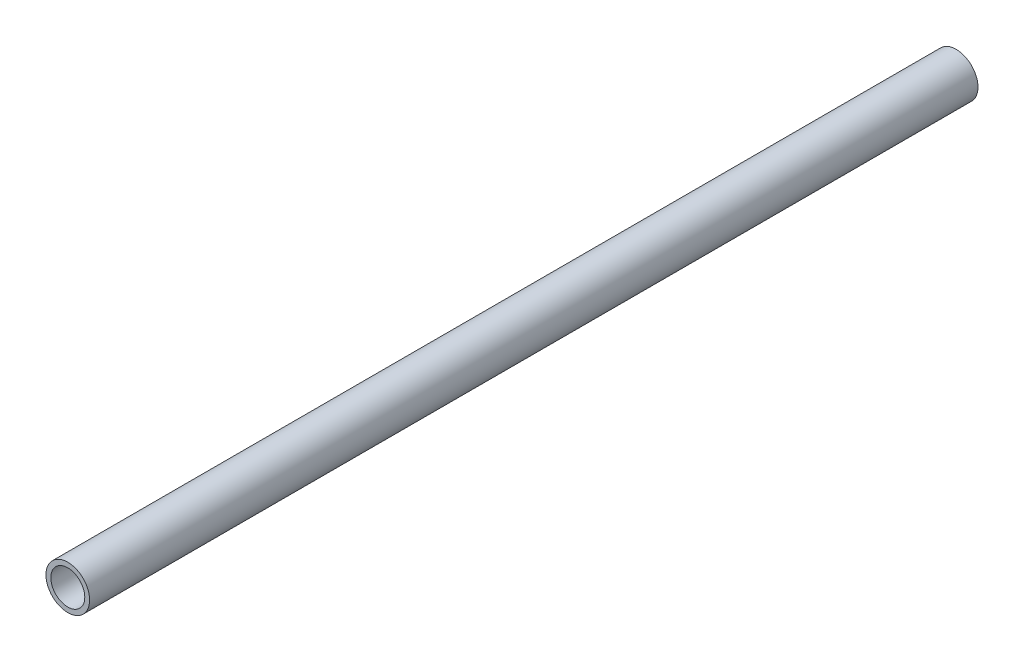
SolidWorks part; units mm, degrees
ref_plane "Front Plane" through (0, 0, 0) normal (0, 0, 1) x (1, 0, 0)
ref_plane "Top Plane" through (0, 0, 0) normal (0, 1, 0) x (1, 0, 0)
ref_plane "Right Plane" through (0, 0, 0) normal (1, 0, 0) x (0, 0, -1)
sketch "Sketch1" plane through (0, 0, 0) normal (0, 0, 1) x (1, 0, 0)
  circle A0 centre (0, 0) radius 9
  circle A1 centre (0, 0) radius 7
  dimension "D1" = 14
  dimension "D2" = 18
extrude "Boss-Extrude1" add sketch "Sketch1" along normal blind 366.18
